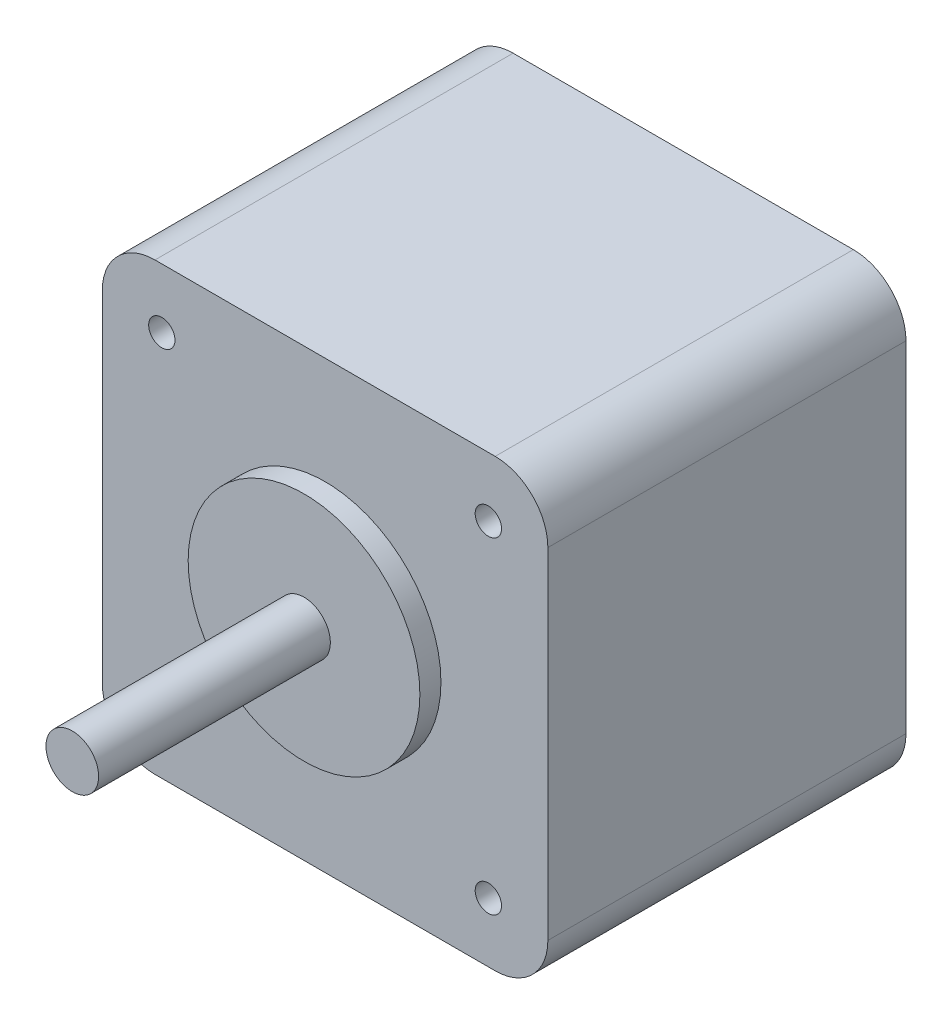
SolidWorks part; units mm, degrees
ref_plane "Ebene vorne" through (0, 0, 0) normal (0, 0, 1) x (1, 0, 0)
ref_plane "Ebene oben" through (0, 0, 0) normal (0, 1, 0) x (1, 0, 0)
ref_plane "Ebene rechts" through (0, 0, 0) normal (1, 0, 0) x (0, 0, -1)
sketch "Skizze1" plane through (0, 0, 0) normal (0, 0, 1) x (1, 0, 0)
  line L1 (5, 0) -> (37.3, 0)
  line L2 (0, 5) -> (0, 37.3)
  line L3 (5, 42.3) -> (37.3, 42.3)
  line L4 (42.3, 5) -> (42.3, 37.3)
  arc A0 (5, 0) -> (0, 5) centre (5, 5) cw
  arc A1 (37.3, 0) -> (42.3, 5) centre (37.3, 5) ccw
  arc A2 (37.3, 42.3) -> (42.3, 37.3) centre (37.3, 37.3) cw
  arc A3 (0, 37.3) -> (5, 42.3) centre (5, 37.3) cw
  point P7 (0, 0)
  point P10 (42.3, 0)
  point P15 (0, 42.3)
  dimension "D3" = 5
  dimension "D1" = 42.3
  dimension "D2" = 42.3
extrude "Aufsatz-Linear austragen1" add sketch "Skizze1" along normal blind 34
sketch "Skizze2" plane through (0, 0, 34) normal (0, 0, 1) x (1, 0, 0)
  circle A0 centre (21.15, 21.15) radius 11
  dimension "D1" = 22
extrude "Aufsatz-Linear austragen2" add sketch "Skizze2" along normal blind 2
sketch "Skizze3" plane through (0, 0, 36) normal (0, 0, 1) x (1, 0, 0)
  circle A0 centre (21.15, 21.15) radius 2.5
  dimension "D1" = 5
extrude "Aufsatz-Linear austragen3" add sketch "Skizze3" along normal blind 22
sketch "Skizze4" plane through (0, 0, 34) normal (0, 0, 1) x (1, 0, 0)
  circle A0 centre (5.65, 36.65) radius 1.818
  circle A1 centre (36.65, 36.65) radius 2.38
  circle A2 centre (36.65, 5.65) radius 1.8867
  circle A3 centre (5.65, 5.65) radius 1.7048
  circle A4 centre (21.15, 21.15) radius 11 construction
  dimension "D1" = 31
  dimension "D2" = 31
  dimension "D3" = 15.5
  dimension "D4" = 15.5
hole_wizard "M3 Gewindebohrung1" positions "3D-Skizze1" profile "Skizze5" tap size "M3" standard "DIN"
sketch3d "3D-Skizze1"
  point P0 (5.65, 36.65, 34)
  point P3 (36.65, 36.65, 34)
  point P6 (36.65, 5.65, 34)
  point P9 (5.65, 5.65, 34)
sketch "Skizze5" plane through (5.65, 36.65, 34) normal (1, 0, 0) x (0, -1, 0)
  line L0 (0, 0) -> (0, 9.2511)
  line L1 (0, 9.2511) -> (1.25, 8.5)
  line L2 (1.25, 8.5) -> (1.25, 0)
  line L5 (1.25, 0) -> (0, 0)
  line L10 (0, 9.2511) -> (-1.25, 8.5) construction
  line L11 (0, -6.35) -> (0, 107.95) construction
  dimension "Bohrerdurchmesser" = 2.5
  dimension "Bohrungstiefe" = 8.5
  dimension "Spitzenwinkel" = 118
cosmetic thread "Bohrungsgewinde1" parameters "D1"=6, "D2"=3
cosmetic thread "Bohrungsgewinde2" parameters "D1"=6, "D2"=3
cosmetic thread "Bohrungsgewinde3" parameters "D1"=6, "D2"=3
cosmetic thread "Bohrungsgewinde4" parameters "D1"=6, "D2"=3
